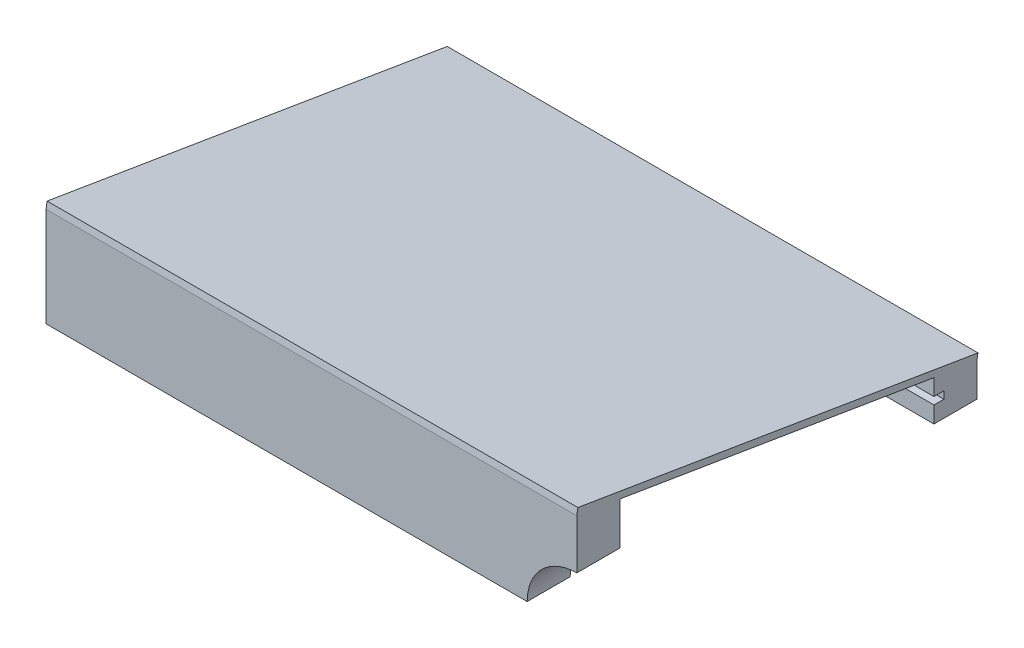
SolidWorks part; units mm, degrees
ref_plane "Front Plane" through (0, 0, 0) normal (0, 0, 1) x (1, 0, 0)
ref_plane "Top Plane" through (0, 0, 0) normal (0, 1, 0) x (1, 0, 0)
ref_plane "Right Plane" through (0, 0, 0) normal (1, 0, 0) x (0, 0, -1)
sketch "Sketch1" plane through (0, 0, 0) normal (0, 1, 0) x (1, 0, 0)
  line L0 (-7.9122, -15.187) -> (-7.9122, 79.813)
  line L1 (-16.9122, -28.187) -> (148.0878, -28.187)
  line L2 (-16.9122, -28.187) -> (-16.9122, 92.813)
  line L3 (-16.9122, 92.813) -> (148.0878, 92.813)
  line L4 (148.0878, -28.187) -> (148.0878, -15.187)
  line L5 (-7.9122, 79.813) -> (148.0878, 79.813)
  line L6 (-7.9122, -15.187) -> (148.0878, -15.187)
  line L7 (148.0878, 79.813) -> (148.0878, 92.813)
  dimension "D1" = 165
  dimension "D2" = 121
  dimension "D3" = 13
  dimension "D4" = 13
  dimension "D5" = 9
extrude "Boss-Extrude1" add sketch "Sketch1" along normal blind 30
sketch "Sketch2" plane through (148.0878, 0, 0) normal (1, 0, 0) x (0, 0, -1)
  line L0 (-15.187, 30) -> (-15.187, 0) construction
  line L1 (-18.187, 7.2) -> (82.813, 7.2)
  line L2 (-18.187, 7.2) -> (-18.187, 5)
  line L3 (-18.187, 5) -> (82.813, 5)
  line L4 (82.813, 7.2) -> (82.813, 5)
  line L5 (79.813, 30) -> (79.813, 0) construction
  line L6 (-28.187, 0) -> (-15.187, 0) construction
  dimension "D1" = 2.2
  dimension "D2" = 3
  dimension "D3" = 3
  dimension "D4" = 5
extrude "Cut-Extrude1" cut sketch "Sketch2" against normal blind 160
sketch "Sketch4" plane through (0, 7.2, 0) normal (0, -1, 0) x (1, 0, 0)
  line L0 (-7.9122, 15.187) -> (-11.9109, 15.187)
  line L1 (-11.9109, 15.187) -> (-11.9109, -79.8159)
  line L2 (-11.9109, -79.8159) -> (-7.9122, -79.813)
  line L3 (-7.9122, 15.187) -> (-7.9122, -79.813) construction
  line L4 (-7.9122, -79.813) -> (148.0878, -79.813) construction
  line L5 (-7.9122, -79.813) -> (-7.9122, 15.187)
extrude "Cut-Extrude2" cut sketch "Sketch4" along normal blind 108
sketch "Sketch5" plane through (-16.9122, 0, 0) normal (-1, 0, 0) x (0, 0, 1)
  line L0 (-92.813, 10) -> (-92.813, 30)
  line L1 (-92.813, 30) -> (-92.813, 0) construction
  line L2 (-92.813, 10) -> (28.187, 30)
  line L3 (-92.813, 30) -> (28.187, 30) construction
  line L4 (28.187, 30) -> (28.187, 0) construction
  line L5 (-92.813, 30) -> (28.187, 30)
extrude "Cut-Extrude3" cut sketch "Sketch5" against normal blind 202
sketch "Sketch6" plane through (0, 24.6671, -4.0772) normal (0, 0.9866, -0.1631) x (1, 0, 0)
  line L0 (-16.9122, 89.9398) -> (-16.9122, -32.7019)
  line L1 (-16.9122, -32.7019) -> (148.0878, -32.7019)
  line L2 (148.0878, -32.7019) -> (148.0878, 89.9398)
  line L3 (148.0878, 89.9398) -> (-16.9122, 89.9398)
extrude "Boss-Extrude2" add sketch "Sketch6" along normal blind 2
sketch "Sketch7" plane through (0, 0, 28.187) normal (0, 0, 1) x (1, 0, 0)
  circle A0 centre (148.0878, 0) radius 15
extrude "Cut-Extrude4" cut sketch "Sketch7" against normal blind 22
sketch "Sketch8" plane through (148.0878, 0, 0) normal (1, 0, 0) x (0, 0, -1)
  line L0 (-28.187, 30) -> (-28.187, 0)
  line L1 (-28.187, 0) -> (92.813, 0)
  line L2 (92.813, 0) -> (92.813, 10)
  line L3 (92.813, 10) -> (93.1392, 11.9732)
  line L4 (93.1392, 11.9732) -> (-27.8608, 31.9732)
  line L5 (-27.8608, 31.9732) -> (-28.187, 30)
extrude "Cut-Extrude5" cut sketch "Sketch8" against normal blind 4.5
sketch "Sketch9" plane through (0, 0, 28.187) normal (0, 0, 1) x (1, 0, 0)
  line L0 (133.0878, 0) -> (143.5878, 0)
  line L1 (143.5878, 0) -> (143.5878, 14.3091)
  line L2 (128.5878, 0) -> (133.0878, 0)
  line L3 (143.5878, 14.3091) -> (143.5878, 15)
  arc A0 (143.5878, 15) -> (128.5878, 0) centre (143.5878, 0) ccw
extrude "Cut-Extrude6" cut sketch "Sketch9" against normal blind 21.5
